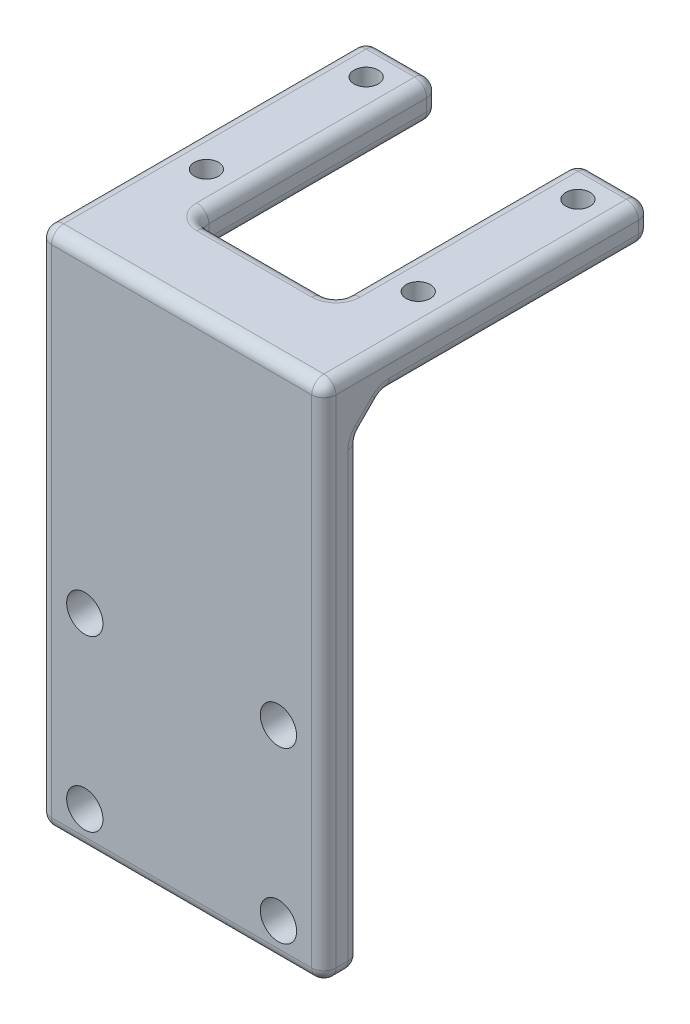
SolidWorks part; units mm, degrees
ref_plane "前视基准面" through (0, 0, 0) normal (0, 0, 1) x (1, 0, 0)
ref_plane "上视基准面" through (0, 0, 0) normal (0, 1, 0) x (1, 0, 0)
ref_plane "右视基准面" through (0, 0, 0) normal (1, 0, 0) x (0, 0, -1)
sketch "草图1" plane through (0, 0, 0) normal (0, 0, 1) x (1, 0, 0)
  line L1 (-11.75, 20) -> (11.75, 20)
  line L2 (-11.75, 20) -> (-11.75, -20)
  line L3 (-11.75, -20) -> (11.75, -20)
  line L4 (11.75, 20) -> (11.75, -20)
  line L5 (-11.75, 20) -> (11.75, -20) construction
  line L6 (-11.75, -20) -> (11.75, 20) construction
  circle A0 centre (-8, -3) radius 1.5
  circle A1 centre (8, -3) radius 1.5
  circle A2 centre (8, -17) radius 1.5
  circle A3 centre (-8, -17) radius 1.5
  point P0 (0, 0)
  dimension "D3" = 23
  dimension "D1" = 23.5
  dimension "D2" = 40
  dimension "D4" = 3.75
  dimension "D5" = 23
  dimension "D6" = 3.75
  dimension "D7" = 3.75
  dimension "D8" = 3
  dimension "D9" = 3
  dimension "D10" = 3.75
  dimension "D11" = 14
extrude "凸台-拉伸1" add sketch "草图1" along normal blind 3
sketch "草图2" plane through (0, 20, 0) normal (0, 1, 0) x (1, 0, 0)
  line L1 (-11.75, 24) -> (11.75, 24)
  line L2 (-11.75, 24) -> (-11.75, -4)
  line L3 (-11.75, -4) -> (11.75, -4)
  line L4 (11.75, 24) -> (11.75, -4)
  line L5 (-11.75, 24) -> (11.75, -4) construction
  line L6 (-11.75, -4) -> (11.75, 24) construction
  line L7 (11.75, 0) -> (-11.75, 0) construction
  line L8 (-5.75, 24) -> (5.75, 24)
  line L9 (-5.75, 24) -> (-5.75, 4)
  line L10 (-5.75, 4) -> (5.75, 4)
  line L11 (5.75, 24) -> (5.75, 4)
  circle A0 centre (-8.75, 21) radius 1
  circle A1 centre (8.75, 21) radius 1
  circle A2 centre (-8.75, 7.8) radius 1
  circle A3 centre (8.75, 7.8) radius 1
  point P0 (0, 10)
  line M5 (11.75, 0) -> (-11.75, 0)
  line M6 (-11.75, 0) -> (-11.75, -3)
  line M7 (-11.75, -3) -> (11.75, -3)
  line M8 (11.75, -3) -> (11.75, 0)
  dimension "D5" = 3
  dimension "D17" = 2
  dimension "D18" = 2
  dimension "D19" = 2
  dimension "D20" = 2
  dimension "D1" = 28
  dimension "D2" = 23.5
  dimension "D3" = 10
  dimension "D4" = 0
  dimension "D6" = 3
  dimension "D7" = 3
  dimension "D8" = 3
  dimension "D9" = 3
  dimension "D10" = 3
  dimension "D11" = 17.5
  dimension "D12" = 13.2
  dimension "D13" = 13.2
  dimension "D14" = 3
  dimension "D15" = 3
  dimension "D16" = 4
extrude "凸台-拉伸2" add sketch "草图2" along normal blind 3 contours L1 L11 L10 L9 L2 L4 A3 A2 A1 A0 M5 | M8 M5 M6 M7
chamfer "倒角1" distance 2 angle 45 1 edges at (0, 20, 0)
fillet "圆角1" radius 1 33 edges at (0, 23, -4) (0, 20, -4) (-8.75, 23, -24) (-8.75, 20, -24) (8.75, 23, -24) (8.75, 20, -24) (5.75, 21.5, -24) (5.75, 23, -14) (5.75, 21.5, -4) (5.75, 20, -14) (-5.75, 21.5, -4) (-5.75, 23, -14) (-5.75, 21.5, -24) (-5.75, 20, -14) (0, 20, -2) (0, 18, 0) (11.75, 1.5, 3) (-11.75, 23, -10.5) (11.75, 23, -10.5) (11.75, 21.5, -24) (-11.75, 21.5, -24) (11.75, 20, -13) (-11.75, 20, -13) (11.75, 19, -1) (11.75, -1, 0) (-11.75, 1.5, 3) (-11.75, -1, 0) (-11.75, 19, -1) (-11.75, -20, 1.5) (0, -20, 3) (11.75, -20, 1.5) (0, -20, 0) (0, 23, 3)
